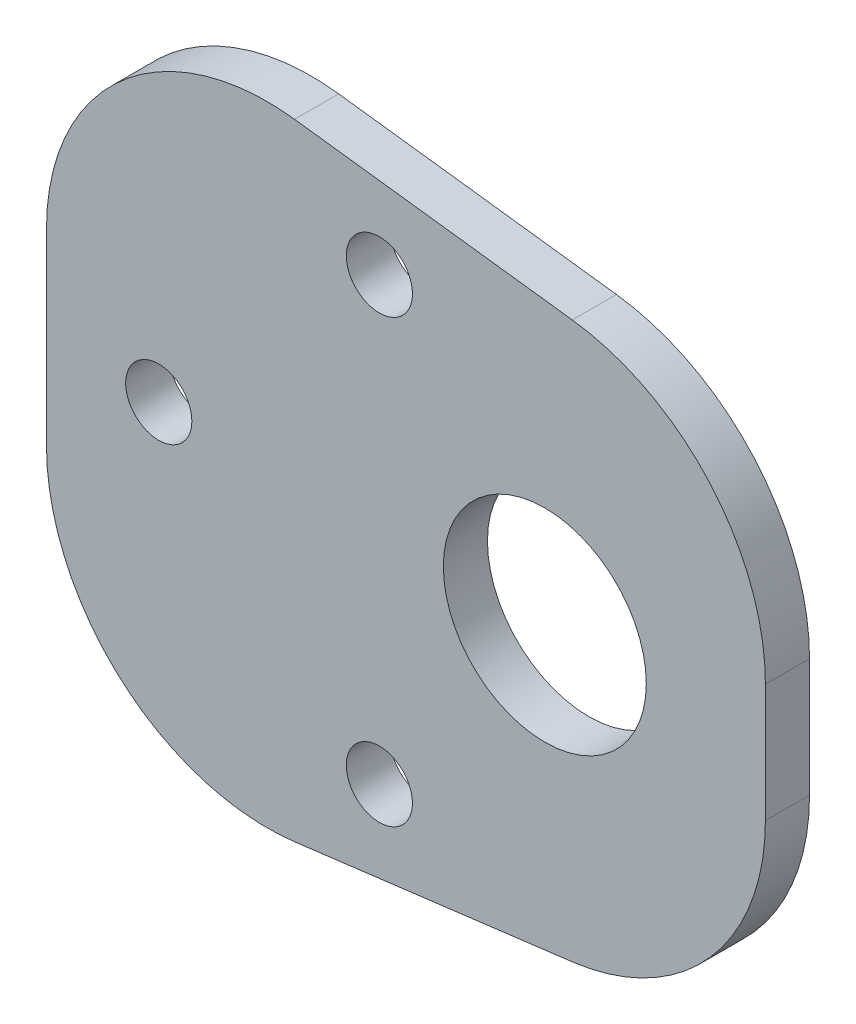
SolidWorks part; units mm, degrees
ref_plane "前视基准面" through (0, 0, 0) normal (0, 0, 1) x (1, 0, 0)
ref_plane "上视基准面" through (0, 0, 0) normal (0, 1, 0) x (1, 0, 0)
ref_plane "右视基准面" through (0, 0, 0) normal (1, 0, 0) x (0, 0, -1)
sketch "草图1" plane through (0, 0, 0) normal (0, 0, 1) x (1, 0, 0)
  line L0 (-22.499, 0) -> (-38.999, 0) construction
  line L12 (-3.7531, 12.6002) -> (-16.3433, 14.1812)
  line L36 (-9.489, 1) -> (-9.489, -1) construction
  line L40 (-0.509, 1) -> (-0.509, -1) construction
  line L41 (-3.7531, -12.6002) -> (-16.3433, -14.1812)
  line L45 (5.001, 2.6782) -> (5.001, -2.6782)
  line L47 (-27.5892, -4.2591) -> (-27.5892, 4.2591)
  circle A3 centre (-38.999, 0) radius 3 construction
  circle A6 centre (-12.499, 10) radius 1.5
  circle A37 centre (-4.999, 0) radius 4.6
  circle A43 centre (-12.499, -10) radius 1.5
  circle A46 centre (-22.499, 0) radius 1.5
  arc A47 (-3.7531, -12.6002) -> (5.001, -2.6782) centre (-4.999, -2.6782) ccw
  arc A48 (-3.7531, 12.6002) -> (5.001, 2.6782) centre (-4.999, 2.6782) cw
  arc A49 (-16.3433, 14.1812) -> (-27.5892, 4.2591) centre (-17.5892, 4.2591) ccw
  arc A50 (-27.5892, -4.2591) -> (-16.3433, -14.1812) centre (-17.5892, -4.2591) ccw
  point P7 (5.001, -11.501)
  point P11 (5.001, 11.501)
  point P14 (-27.5892, 15.5933)
  point P22 (-27.5892, -15.5933)
  dimension "D3" = 10
  dimension "D4" = 10
  dimension "D5" = 9.2
  dimension "D6" = 10
  dimension "D2" = 10
  dimension "D1" = 16.5
extrude "凸台-拉伸1" add sketch "草图1" along normal blind 2
